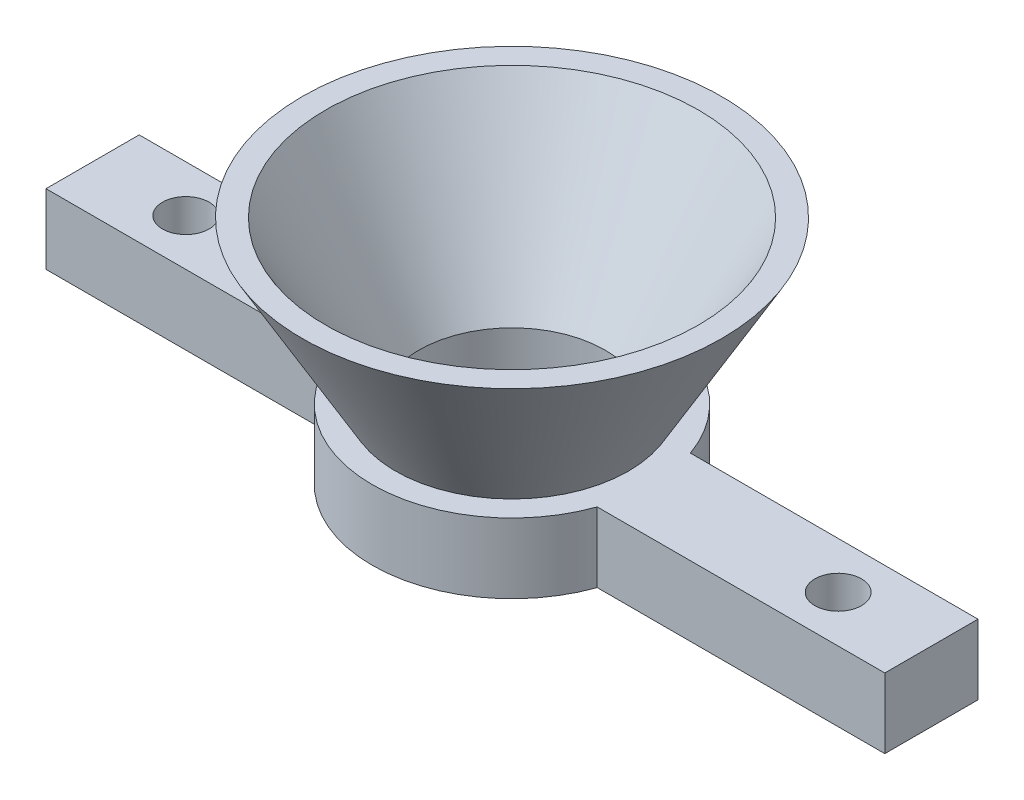
SolidWorks part; units mm, degrees
ref_plane "Front Plane" through (0, 0, 0) normal (0, 0, 1) x (1, 0, 0)
ref_plane "Top Plane" through (0, 0, 0) normal (0, 1, 0) x (1, 0, 0)
ref_plane "Right Plane" through (0, 0, 0) normal (1, 0, 0) x (0, 0, -1)
sketch "Sketch1" plane through (0, 0, 0) normal (0, 1, 0) x (1, 0, 0)
  line L0 (0, 0) -> (4.7625, 0)
  line L1 (-14.2875, -1.5875) -> (14.2875, -1.5875)
  line L2 (-14.2875, -1.5875) -> (-14.2875, 1.5875)
  line L3 (-14.2875, 1.5875) -> (14.2875, 1.5875)
  line L4 (14.2875, -1.5875) -> (14.2875, 1.5875)
  line L5 (-14.2875, -1.5875) -> (14.2875, 1.5875) construction
  line L6 (-14.2875, 1.5875) -> (14.2875, -1.5875) construction
  line L7 (4.7625, 0) -> (-4.7625, 0)
  line L8 (-3.175, 0) -> (-5.9246, -1.5875)
  line L9 (-5.9246, -1.5875) -> (5.9246, -1.5875)
  line L10 (5.9246, -1.5875) -> (3.175, 0)
  circle A0 centre (0, 0) radius 4.7625
  circle A1 centre (0, 0) radius 3.175
  circle A2 centre (-11.1125, 0) radius 0.7937
  circle A3 centre (11.1125, 0) radius 0.7937
  point P0 (0, 0)
  dimension "D3" = 1.5875
  dimension "D4" = 9.525
  dimension "D6" = 1.5875
  dimension "D7" = 3.175
  dimension "D1" = 28.575
  dimension "D2" = 3.175
  dimension "D5" = 3.175
  dimension "D8" = 3.175
extrude "Boss-Extrude1" add sketch "Sketch1" along normal mid plane 2.3813 contours A0 L3 L2 L1 L8 A2 | A1 L3 A0 | A0 L10 L1 L4 L3 A3 | A1 L7 A0 L3 | L10 A0 L7 | A1 L9 A0 L10 | A1 L9 A0 | A1 L8 A0 L9 | A1 L3 A0 L7 | L7 A0 L8 | A0 L1 L10 | A0 L8 L1
sketch "Sketch2" plane through (0, 0, 0) normal (0, 0, 1) x (1, 0, 0)
  line L3 (-14.2875, 1.1906) -> (-4.4901, 1.1906) construction
  line L4 (0, -1000) -> (0, 49000) construction
  line L5 (-3.175, 1.1906) -> (-6.35, 6.6899)
  line L9 (-3.175, 1.1906) -> (-3.9688, 1.1906)
  line L10 (-6.35, 6.6899) -> (-7.1438, 6.6899)
  line L11 (-3.9688, 1.1906) -> (-7.1438, 6.6899)
  point P0 (-6.5485, 6.993)
  dimension "D1" = 6.35
  dimension "D2" = 0.7937
  dimension "D3" = 60
revolve "Revolve2" add sketch "Sketch2" angle 360 about L4
